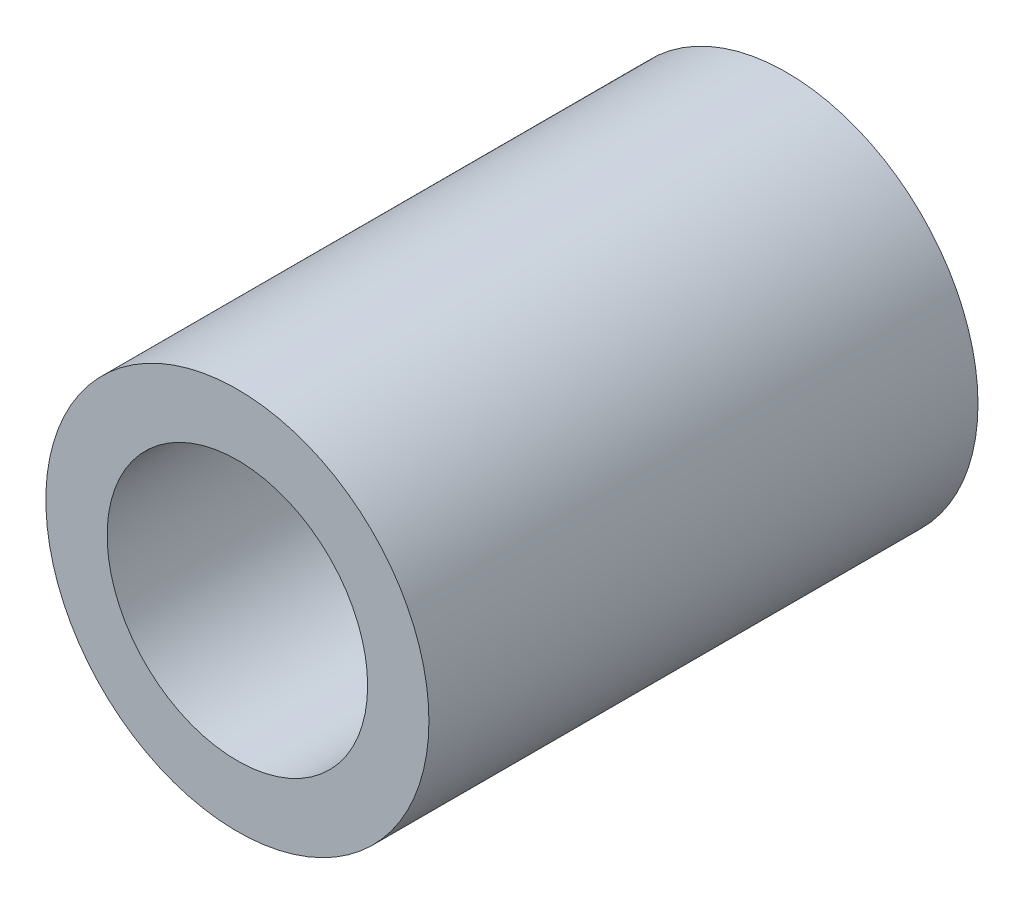
SolidWorks part; units mm, degrees
ref_plane "前视基准面" through (0, 0, 0) normal (0, 0, 1) x (1, 0, 0)
ref_plane "上视基准面" through (0, 0, 0) normal (0, 1, 0) x (1, 0, 0)
ref_plane "右视基准面" through (0, 0, 0) normal (1, 0, 0) x (0, 0, -1)
sketch "草图1" plane through (0, 0, 0) normal (0, 0, 1) x (1, 0, 0)
  circle A0 centre (0, 0) radius 5.1
  circle A1 centre (0, 0) radius 7.5
  dimension "D1" = 10.2
  dimension "D2" = 15
extrude "凸台-拉伸1" add sketch "草图1" along normal blind 21.5
